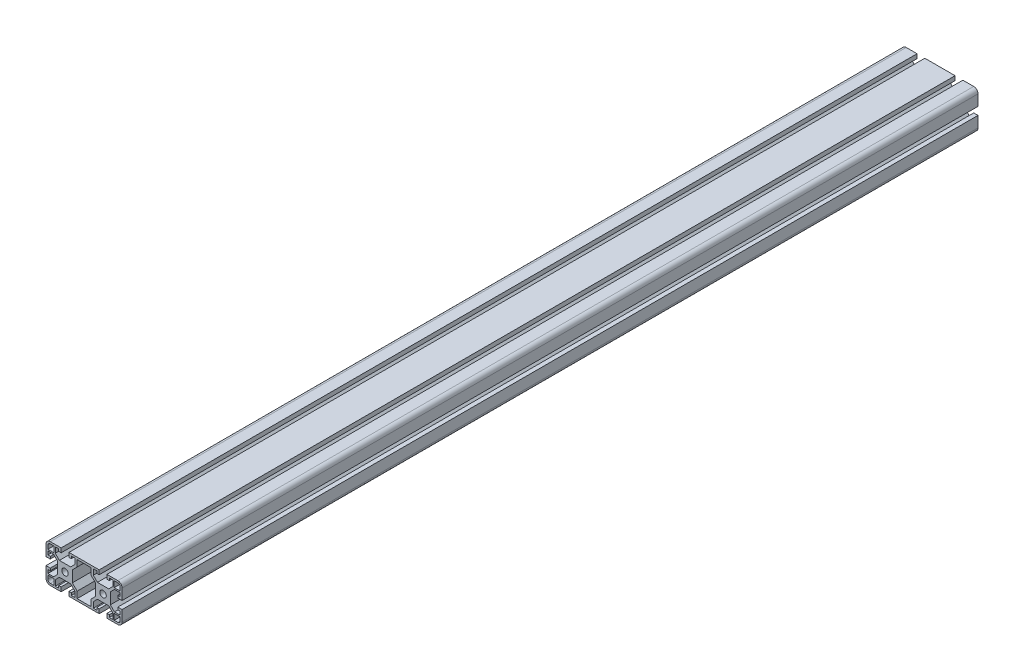
SolidWorks part; units mm, degrees
ref_plane "Front Plane" through (0, 0, 0) normal (0, 0, 1) x (1, 0, 0)
ref_plane "Top Plane" through (0, 0, 0) normal (0, 1, 0) x (1, 0, 0)
ref_plane "Right Plane" through (0, 0, 0) normal (1, 0, 0) x (0, 0, -1)
sketch "Sketch1" plane through (0, 0, 0) normal (0, 0, 1) x (1, 0, 0)
  line L0 (0, 17.8) -> (0, -17.8) construction
  line B0 (38, -15.5) -> (38, -11.75)
  line B1 (38, -11.75) -> (31.75, -11.75)
  line B2 (31.75, -11.75) -> (31.75, -18)
  line B3 (31.75, -18) -> (35.5, -18)
  arc B4 (35.5, -18) -> (38, -15.5) centre (35.5, -15.5) ccw
  line B5 (-38, 15.5) -> (-38, 11.75)
  line B6 (-38, 11.75) -> (-31.75, 11.75)
  line B7 (-31.75, 11.75) -> (-31.75, 18)
  line B8 (-31.75, 18) -> (-35.5, 18)
  arc B9 (-35.5, 18) -> (-38, 15.5) centre (-35.5, 15.5) ccw
  line B10 (24.1, -20) -> (35.5, -20)
  arc B11 (35.5, -20) -> (40, -15.5) centre (35.5, -15.5) ccw
  line B12 (40, -15.5) -> (40, -4.1)
  line B13 (40, -4.1) -> (35.5, -4.1)
  line B14 (35.5, -4.1) -> (35.5, -6.6)
  line B15 (35.5, -6.6) -> (38, -6.6)
  line B16 (38, -6.6) -> (38, -10.25)
  line B17 (38, -10.25) -> (32.0178, -10.25)
  line B18 (32.0178, -10.25) -> (27.7, -5.9322)
  line B19 (27.7, -5.9322) -> (27.7, 5.9322)
  line B20 (27.7, 5.9322) -> (32.0178, 10.25)
  line B21 (32.0178, 10.25) -> (38, 10.25)
  line B22 (38, 10.25) -> (38, 6.6)
  line B23 (38, 6.6) -> (35.5, 6.6)
  line B24 (35.5, 6.6) -> (35.5, 4.1)
  line B25 (35.5, 4.1) -> (40, 4.1)
  line B26 (40, 4.1) -> (40, 15.5)
  arc B27 (40, 15.5) -> (35.5, 20) centre (35.5, 15.5) ccw
  line B28 (35.5, 20) -> (24.1, 20)
  line B29 (24.1, 20) -> (24.1, 15.5)
  line B30 (24.1, 15.5) -> (26.6, 15.5)
  line B31 (26.6, 15.5) -> (26.6, 18)
  line B32 (26.6, 18) -> (30.25, 18)
  line B33 (30.25, 18) -> (30.25, 12.0178)
  line B34 (30.25, 12.0178) -> (25.9322, 7.7)
  line B35 (25.9322, 7.7) -> (14.0678, 7.7)
  line B36 (14.0678, 7.7) -> (9.75, 12.0178)
  line B37 (9.75, 12.0178) -> (9.75, 18)
  line B38 (9.75, 18) -> (13.4, 18)
  line B39 (13.4, 18) -> (13.4, 15.5)
  line B40 (13.4, 15.5) -> (15.9, 15.5)
  line B41 (15.9, 15.5) -> (15.9, 20)
  line B42 (15.9, 20) -> (-15.9, 20)
  line B43 (-15.9, 20) -> (-15.9, 15.5)
  line B44 (-15.9, 15.5) -> (-13.4, 15.5)
  line B45 (-13.4, 15.5) -> (-13.4, 18)
  line B46 (-13.4, 18) -> (-9.75, 18)
  line B47 (-9.75, 18) -> (-9.75, 12.0178)
  line B48 (-9.75, 12.0178) -> (-14.0678, 7.7)
  line B49 (-14.0678, 7.7) -> (-25.9322, 7.7)
  line B50 (-25.9322, 7.7) -> (-30.25, 12.0178)
  line B51 (-30.25, 12.0178) -> (-30.25, 18)
  line B52 (-30.25, 18) -> (-26.6, 18)
  line B53 (-26.6, 18) -> (-26.6, 15.5)
  line B54 (-26.6, 15.5) -> (-24.1, 15.5)
  line B55 (-24.1, 15.5) -> (-24.1, 20)
  line B56 (-24.1, 20) -> (-35.5, 20)
  arc B57 (-35.5, 20) -> (-40, 15.5) centre (-35.5, 15.5) ccw
  line B58 (-40, 15.5) -> (-40, 4.1)
  line B59 (-40, 4.1) -> (-35.5, 4.1)
  line B60 (-35.5, 4.1) -> (-35.5, 6.6)
  line B61 (-35.5, 6.6) -> (-38, 6.6)
  line B62 (-38, 6.6) -> (-38, 10.25)
  line B63 (-38, 10.25) -> (-32.0178, 10.25)
  line B64 (-32.0178, 10.25) -> (-27.7, 5.9322)
  line B65 (-27.7, 5.9322) -> (-27.7, -5.9322)
  line B66 (-27.7, -5.9322) -> (-32.0178, -10.25)
  line B67 (-32.0178, -10.25) -> (-38, -10.25)
  line B68 (-38, -10.25) -> (-38, -6.6)
  line B69 (-38, -6.6) -> (-35.5, -6.6)
  line B70 (-35.5, -6.6) -> (-35.5, -4.1)
  line B71 (-35.5, -4.1) -> (-40, -4.1)
  line B72 (-40, -4.1) -> (-40, -15.5)
  arc B73 (-40, -15.5) -> (-35.5, -20) centre (-35.5, -15.5) ccw
  line B74 (-35.5, -20) -> (-24.1, -20)
  line B75 (-24.1, -20) -> (-24.1, -15.5)
  line B76 (-24.1, -15.5) -> (-26.6, -15.5)
  line B77 (-26.6, -15.5) -> (-26.6, -18)
  line B78 (-26.6, -18) -> (-30.25, -18)
  line B79 (-30.25, -18) -> (-30.25, -12.0178)
  line B80 (-30.25, -12.0178) -> (-25.9322, -7.7)
  line B81 (-25.9322, -7.7) -> (-14.0678, -7.7)
  line B82 (-14.0678, -7.7) -> (-9.75, -12.0178)
  line B83 (-9.75, -12.0178) -> (-9.75, -18)
  line B84 (-9.75, -18) -> (-13.4, -18)
  line B85 (-13.4, -18) -> (-13.4, -15.5)
  line B86 (-13.4, -15.5) -> (-15.9, -15.5)
  line B87 (-15.9, -15.5) -> (-15.9, -20)
  line B88 (-15.9, -20) -> (15.9, -20)
  line B89 (15.9, -20) -> (15.9, -15.5)
  line B90 (15.9, -15.5) -> (13.4, -15.5)
  line B91 (13.4, -15.5) -> (13.4, -18)
  line B92 (13.4, -18) -> (9.75, -18)
  line B93 (9.75, -18) -> (9.75, -12.0178)
  line B94 (9.75, -12.0178) -> (14.0678, -7.7)
  line B95 (14.0678, -7.7) -> (25.9322, -7.7)
  line B96 (25.9322, -7.7) -> (30.25, -12.0178)
  line B97 (30.25, -12.0178) -> (30.25, -18)
  line B98 (30.25, -18) -> (26.6, -18)
  line B99 (26.6, -18) -> (26.6, -15.5)
  line B100 (26.6, -15.5) -> (24.1, -15.5)
  line B101 (24.1, -15.5) -> (24.1, -20)
  line B102 (-7.25, -10.9822) -> (-7.25, -17.8)
  line B103 (-7.25, -17.8) -> (7.25, -17.8)
  line B104 (7.25, -17.8) -> (7.25, -10.9822)
  line B105 (7.25, -10.9822) -> (12.3, -5.9322)
  line B106 (12.3, -5.9322) -> (12.3, 5.9322)
  line B107 (12.3, 5.9322) -> (7.25, 10.9822)
  line B108 (7.25, 10.9822) -> (7.25, 17.8)
  line B109 (7.25, 17.8) -> (-7.25, 17.8)
  line B110 (-7.25, 17.8) -> (-7.25, 10.9822)
  line B111 (-7.25, 10.9822) -> (-12.3, 5.9322)
  line B112 (-12.3, 5.9322) -> (-12.3, -5.9322)
  line B113 (-12.3, -5.9322) -> (-7.25, -10.9822)
  circle B114 centre (-20, 0) radius 3.4
  circle B115 centre (20, 0) radius 3.4
  line B116 (-35.5, -18) -> (-31.75, -18)
  line B117 (-31.75, -18) -> (-31.75, -11.75)
  line B118 (-31.75, -11.75) -> (-38, -11.75)
  line B119 (-38, -11.75) -> (-38, -15.5)
  arc B120 (-38, -15.5) -> (-35.5, -18) centre (-35.5, -15.5) ccw
  line B121 (35.5, 18) -> (31.75, 18)
  line B122 (31.75, 18) -> (31.75, 11.75)
  line B123 (31.75, 11.75) -> (38, 11.75)
  line B124 (38, 11.75) -> (38, 15.5)
  arc B125 (38, 15.5) -> (35.5, 18) centre (35.5, 15.5) ccw
sketch_block_instance "S8-4080-1"
sketch_block "S8-4080"
extrude "Boss-Extrude1" add sketch "Sketch1" along normal blind 900
